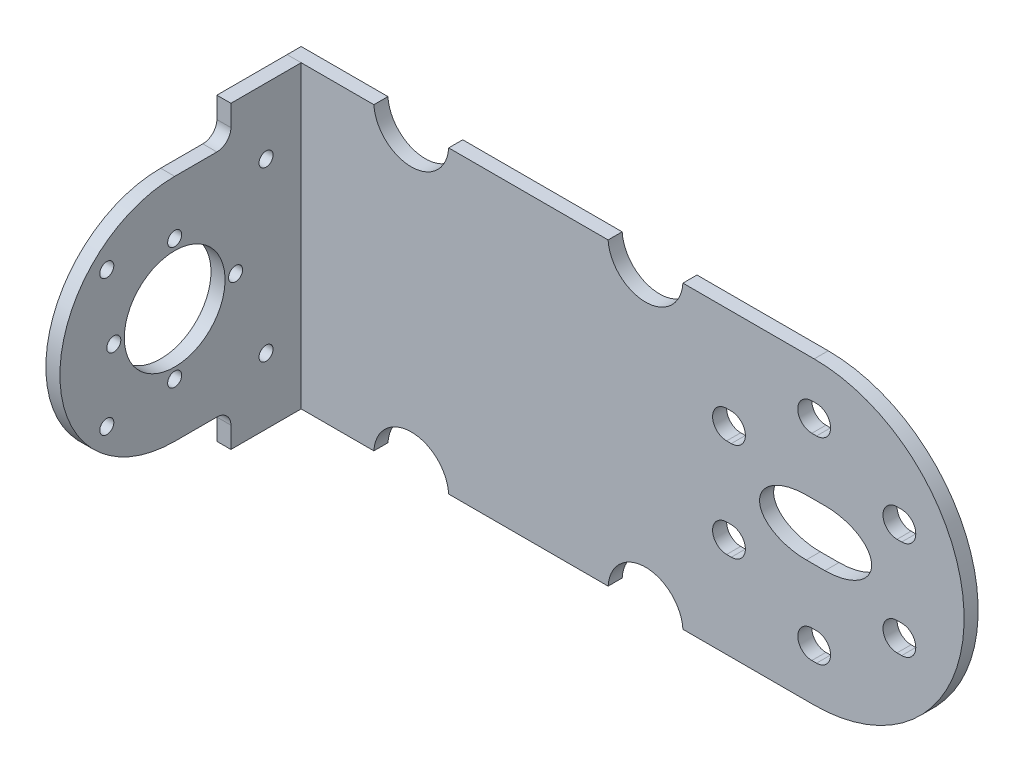
SolidWorks part; units mm, degrees
material "1060 Alloy"
ref_plane "Front Plane" through (0, 0, 0) normal (0, 0, 1) x (1, 0, 0)
ref_plane "Top Plane" through (0, 0, 0) normal (0, 1, 0) x (1, 0, 0)
ref_plane "Right Plane" through (0, 0, 0) normal (1, 0, 0) x (0, 0, -1)
sketch "Sketch1" plane through (0, 0, 0) normal (0, 0, 1) x (1, 0, 0)
  line L0 (-112.5, 32) -> (0, 32)
  line L1 (-112.5, -32) -> (0, -32)
  line L2 (17.6865, 10.5) -> (18.6865, 10.5) construction
  line L3 (-112.5, 32) -> (-112.5, -32)
  line L4 (-113, -33) -> (-113, 33) construction
  line L7 (17.6865, 13.5) -> (18.6865, 13.5)
  line L8 (17.6865, 7.5) -> (18.6865, 7.5)
  line L9 (17.6865, -10.5) -> (18.6865, -10.5) construction
  line L10 (17.6865, -7.5) -> (18.6865, -7.5)
  line L11 (17.6865, -13.5) -> (18.6865, -13.5)
  line L12 (-0.5, -21) -> (0.5, -21) construction
  line L13 (-0.5, -18) -> (0.5, -18)
  line L14 (-0.5, -24) -> (0.5, -24)
  line L15 (-18.6865, -10.5) -> (-17.6865, -10.5) construction
  line L16 (-18.6865, -7.5) -> (-17.6865, -7.5)
  line L17 (-18.6865, -13.5) -> (-17.6865, -13.5)
  line L18 (-17.6865, 10.5) -> (-18.6865, 10.5) construction
  line L19 (-17.6865, 7.5) -> (-18.6865, 7.5)
  line L20 (-17.6865, 13.5) -> (-18.6865, 13.5)
  line L21 (0.5, 21) -> (-0.5, 21) construction
  line L22 (0.5, 18) -> (-0.5, 18)
  line L23 (0.5, 24) -> (-0.5, 24)
  arc A1 (17.6865, 13.5) -> (17.6865, 7.5) centre (17.6865, 10.5) ccw
  circle A2 centre (18.1865, -10.5) radius 3 construction
  circle A3 centre (0, -21) radius 3 construction
  circle A4 centre (-18.1865, -10.5) radius 3 construction
  circle A5 centre (-18.1865, 10.5) radius 3 construction
  circle A6 centre (0, 21) radius 3 construction
  arc A7 (0, -32) -> (0, 32) centre (0, 0) ccw
  arc A11 (18.6865, 7.5) -> (18.6865, 13.5) centre (18.6865, 10.5) ccw
  circle A12 centre (18.1865, 10.5) radius 3 construction
  arc A13 (17.6865, -7.5) -> (17.6865, -13.5) centre (17.6865, -10.5) ccw
  arc A14 (18.6865, -13.5) -> (18.6865, -7.5) centre (18.6865, -10.5) ccw
  arc A15 (-0.5, -18) -> (-0.5, -24) centre (-0.5, -21) ccw
  arc A16 (0.5, -24) -> (0.5, -18) centre (0.5, -21) ccw
  arc A17 (-18.6865, -7.5) -> (-18.6865, -13.5) centre (-18.6865, -10.5) ccw
  arc A18 (-17.6865, -13.5) -> (-17.6865, -7.5) centre (-17.6865, -10.5) ccw
  arc A19 (-17.6865, 7.5) -> (-17.6865, 13.5) centre (-17.6865, 10.5) ccw
  arc A20 (-18.6865, 13.5) -> (-18.6865, 7.5) centre (-18.6865, 10.5) ccw
  arc A21 (0.5, 18) -> (0.5, 24) centre (0.5, 21) ccw
  arc A22 (-0.5, 24) -> (-0.5, 18) centre (-0.5, 21) ccw
  circle A23 centre (18.1865, -10.5) radius 3 construction
  circle A24 centre (0, -21) radius 3 construction
  circle A25 centre (-18.1865, -10.5) radius 3 construction
  circle A26 centre (-18.1865, 10.5) radius 3 construction
  circle A27 centre (0, 21) radius 3 construction
  arc A28 (0, -33) -> (0, 33) centre (0, 0) ccw construction
  point P3 (18.1865, 10.5)
  point P18 (0, 0)
  point P33 (18.1865, -10.5)
  point P41 (0, -21)
  point P48 (-18.1865, -10.5)
  point P56 (-18.1865, 10.5)
  point P62 (0, 21)
  dimension "D2" = 1
  dimension "D3" = 0.5
  dimension "D1" = 1
extrude "Boss-Extrude1" add sketch "Sketch1" along normal blind 3 contours A7 L0 L3 L1
sketch "Sketch2" plane through (-112.5, 0, 0) normal (-1, 0, 0) x (0, 0, 1)
  line L0 (3, -32) -> (18, -32)
  line L1 (18, -32) -> (18, -27.5)
  line L2 (21, -24.5) -> (30, -24.5)
  line L3 (0, 0) -> (46.5, 0) construction
  line L4 (3, 32) -> (18, 32)
  line L5 (18, 32) -> (18, 27.5)
  line L6 (21, 24.5) -> (30, 24.5)
  line L7 (44.4957, 14.4957) -> (30, 0) construction
  line L8 (54.5, 0) -> (46.5, 0) construction
  line L9 (17.8585, -11.1729) -> (3.1415, -24.7158) construction
  line L10 (17.8585, -11.1729) -> (30, 0) construction
  circle A0 centre (30, 0) radius 36.5 construction
  circle A2 centre (10.5, -17.9444) radius 1.5
  circle A3 centre (30, 13) radius 1.5
  circle A4 centre (30, 13) radius 1.5 construction
  circle A5 centre (43, 0) radius 1.5
  circle A6 centre (30, -13) radius 1.5
  circle A7 centre (17, 0) radius 1.5
  circle A10 centre (30, 0) radius 10.75
  arc A11 (18, -27.5) -> (21, -24.5) centre (21, -27.5) cw
  arc A12 (18, 27.5) -> (21, 24.5) centre (21, 27.5) ccw
  circle A13 centre (10.5, 17.9444) radius 1.5
  arc A15 (27, -24.3156) -> (27, 24.3156) centre (30, 0) ccw construction
  arc A17 (30, -24.5) -> (30, 24.5) centre (30, 0) ccw
  circle A18 centre (30, 0) radius 10.5 construction
  circle A19 centre (30, 0) radius 16.5 construction
  circle A20 centre (30, 0) radius 20.5 construction
  circle A21 centre (30, 0) radius 36.5 construction
  circle A22 centre (44.4957, 14.4957) radius 1.5
  circle A23 centre (44.4957, -14.4957) radius 1.5
  point P23 (50.5, 0)
  point P34 (30, 0)
  point P58 (10.5, -17.9444)
  point P62 (10.5, -32)
  dimension "D1" = 4
  dimension "D4" = 0.25
  dimension "D5" = 3
  dimension "D7" = 3
  dimension "D2" = 15
  dimension "D6" = 45
  dimension "D3" = 4
extrude "Boss-Extrude2" add sketch "Sketch2" against normal blind 3 separate body
ref_plane "Plane1" through (-68.3993, 0, -51.5425) normal (0.7986, 0, 0.6018) x (0, 1, 0)
sketch "Sketch3" plane through (-68.3993, 0, -51.5425) normal (0.7986, 0, 0.6018) x (0, 1, 0)
  circle A0 centre (0, 1.0136) radius 6
  circle A1 centre (0, 1.0136) radius 6 construction
extrude "Cut-Extrude1" cut sketch "Sketch3" along normal through all
sketch "Sketch4" plane through (0, 0, 3) normal (0, 0, 1) x (1, 0, 0)
  line L0 (2.2968, -6) -> (-1.6843, -6)
  line L2 (-1.6843, 6) -> (2.2968, 6)
  ellipse E0 centre (-1.6843, 0) end of major axis (-11.6542, 0) minor radius 6 (-1.6843, 6) -> (-1.6843, -6) ccw
  ellipse E1 centre (-1.6843, 0) end of major axis (-11.6542, 0) minor radius 6 construction
  ellipse E3 centre (2.2968, 0) end of major axis (12.2667, 0) minor radius 6 (2.2968, -6) -> (2.2968, 6) ccw
  ellipse E4 centre (2.2968, 0) end of major axis (-7.673, 0) minor radius 6 construction
extrude "Cut-Extrude2" cut sketch "Sketch4" against normal through all
sketch "Sketch5" plane through (0, 0, 3) normal (0, 0, 1) x (1, 0, 0)
  line L0 (-78.0156, 33) -> (-43.9844, 33)
  line L1 (-43.4833, 33) -> (-78.5167, 33) construction
  line L2 (-78.0156, -33) -> (-43.9844, -33)
  line L5 (-86, 40.5) -> (-36, 40.5)
  line L6 (0, 0) -> (-109.5, 0) construction
  line L7 (-109.5, -24.5) -> (-109.5, 24.5) construction
  line L8 (-86, -40.5) -> (-36, -40.5)
  circle A2 centre (-36, -32.5) radius 8
  circle A3 centre (-86, -32.5) radius 8
  circle A9 centre (-86, 32.5) radius 8
  circle A10 centre (-36, 32.5) radius 8
  line M31 (-112.5, -32) -> (0, -32)
  line M33 (0, 32) -> (-112.5, 32)
  dimension "D1" = 16
extrude "Cut-Extrude4" cut sketch "Sketch5" against normal up to surface (3 mm away) contours A10 L5 A9 L0 | A9 M33 | A10 M33 | A3 M31 | L2 A3 L8 A2 | A2 M31 up to face at (0.3063, 0, 0)
